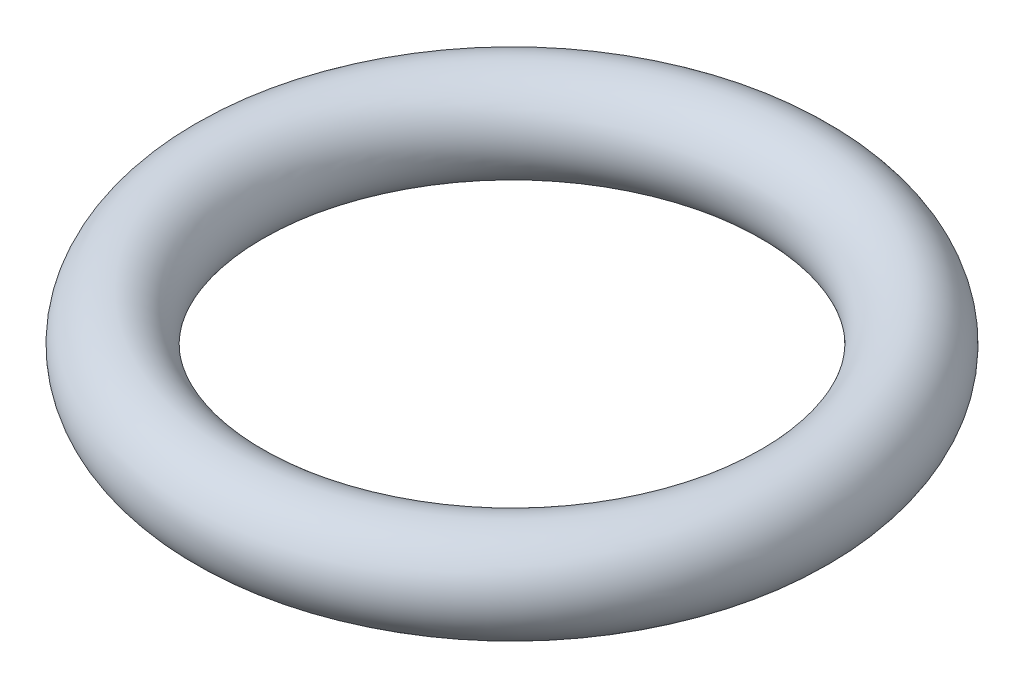
SolidWorks part; units mm, degrees
material "橡胶"
ref_plane "前视基准面" through (0, 0, 0) normal (0, 0, 1) x (1, 0, 0)
ref_plane "上视基准面" through (0, 0, 0) normal (0, 1, 0) x (1, 0, 0)
ref_plane "右视基准面" through (0, 0, 0) normal (1, 0, 0) x (0, 0, -1)
other "Configuration Table"
sketch "草图1" plane through (0, 0, 0) normal (0, 0, 1) x (1, 0, 0)
  line L0 (0, -113.7181) -> (0, 5572.1885) construction
  circle A0 centre (6, 0) radius 1
  point P1 (6, 0)
  dimension "D2" = 2
  dimension "D1" = 6
revolve "旋转1" add sketch "草图1" angle 360 about L0
